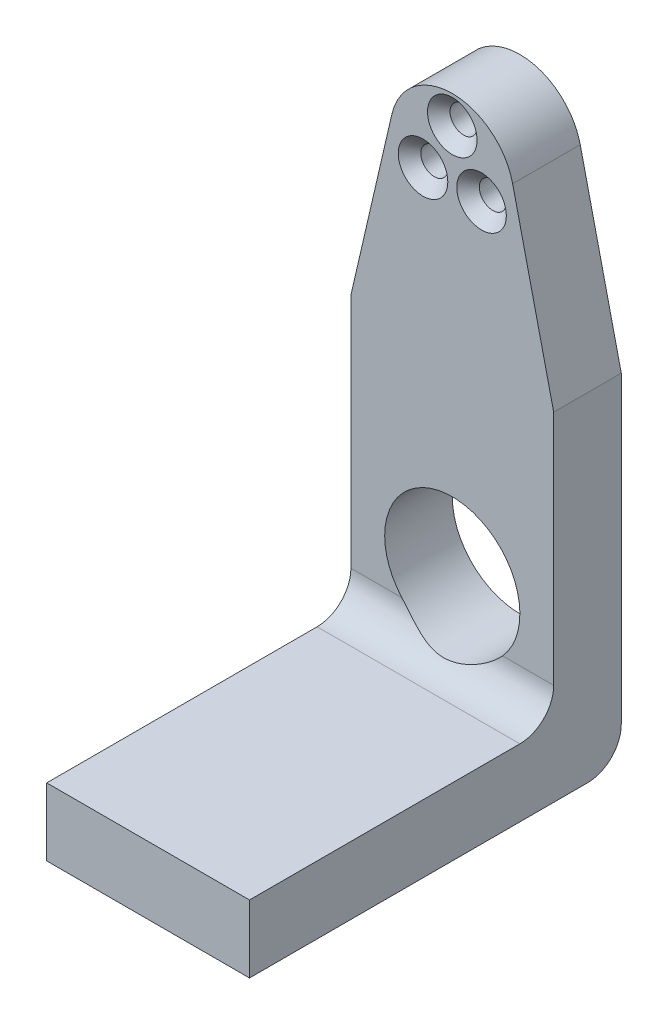
SolidWorks part; units mm, degrees
ref_plane "Plano frontal" through (0, 0, 0) normal (0, 0, 1) x (1, 0, 0)
ref_plane "Plano superior" through (0, 0, 0) normal (0, 1, 0) x (1, 0, 0)
ref_plane "Plano direito" through (0, 0, 0) normal (1, 0, 0) x (0, 0, -1)
sketch "Esboço1" plane through (0, 0, 0) normal (0, 0, 1) x (1, 0, 0)
  line L0 (-9, 30) -> (-9, 0)
  line L1 (-9, 0) -> (9, 0)
  line L2 (9, 0) -> (9, 30)
  line L3 (-5.3585, 45.7397) -> (-9, 30)
  line L4 (5.3585, 45.7397) -> (9, 30)
  arc A1 (-5.3585, 45.7397) -> (5.3585, 45.7397) centre (0, 44.5) cw
  point P4 (0, 0)
  point P12 (0, 50)
  dimension "D1" = 18
  dimension "D3" = 5.5
  dimension "D2" = 30
  dimension "D4" = 50
extrude "Ressalto-extrusão1" add sketch "Esboço1" along normal blind 6
sketch "Esboço2" plane through (0, 0, 6) normal (0, 0, 1) x (1, 0, 0)
  line L0 (9, 0) -> (9, 30) construction
  line L1 (-9, 0) -> (9, 0)
  line L2 (-9, 0) -> (-9, 6)
  line L3 (-9, 6) -> (9, 6)
  line L4 (9, 0) -> (9, 6)
  dimension "D1" = 6
extrude "Ressalto-extrusão2" add sketch "Esboço2" along normal offset from surface (27 mm away) 33 up to face at (0, 25.9566, 0)
fillet "Filete1" radius 3 2 edges at (0, 6, 6) (0, 0, 0)
sketch "Esboço4" plane through (0, 0, 0) normal (0, 0, -1) x (-1, 0, 0)
  line L0 (0, 0) -> (0, 13) construction
  circle A0 centre (0, 13) radius 6
  dimension "D2" = 12
  dimension "D1" = 13
extrude "Corte-extrusão1" cut sketch "Esboço4" against normal blind 33
sketch "Esboço7" plane through (0, 0, 6) normal (0, 0, 1) x (1, 0, 0)
  arc A0 (5.3585, 45.7397) -> (-5.3585, 45.7397) centre (0, 44.5) ccw construction
  circle A1 centre (0, 44.5) radius 3 construction
  point P0 (0, 44.5)
  point P1 (0, 47.5)
  dimension "D1" = 6
hole_wizard "Escareado para parafuso de máquina com cabeça chata de M22" positions "3DSketch2" profile "Esboço8" countersink size "M2" standard "Ansi Metric" end condition through all
sketch3d "3DSketch2"
  point P0 (0, 47.5, 6)
sketch "Esboço8" plane through (0, 47.5, 6) normal (1, 0, 0) x (0, -1, 0)
  line L0 (0, 0) -> (0, 6)
  line L1 (0, 6) -> (1.2, 6)
  line L2 (1.2, 6) -> (1.2, 1)
  line L3 (1.2, 1) -> (2.2, 0)
  line L5 (2.2, 0) -> (0, 0)
  line L6 (-1.2, 1) -> (-2.2, 0) construction
  line L11 (0, -6.35) -> (0, 107.95) construction
  dimension "Thru Hole Dia." = 2.4
  dimension "Thru Hole Depth" = 6
  dimension "Near C'Sink Dia." = 4.4
  dimension "Near C'Sink Angle" = 90
pattern_circular "PadrãoCircular1" count 3 over 360 about axis through (0, 44.5, 0) along (0, 0, 1) of "Escareado para parafuso de máquina com cabeça chata de M22"
